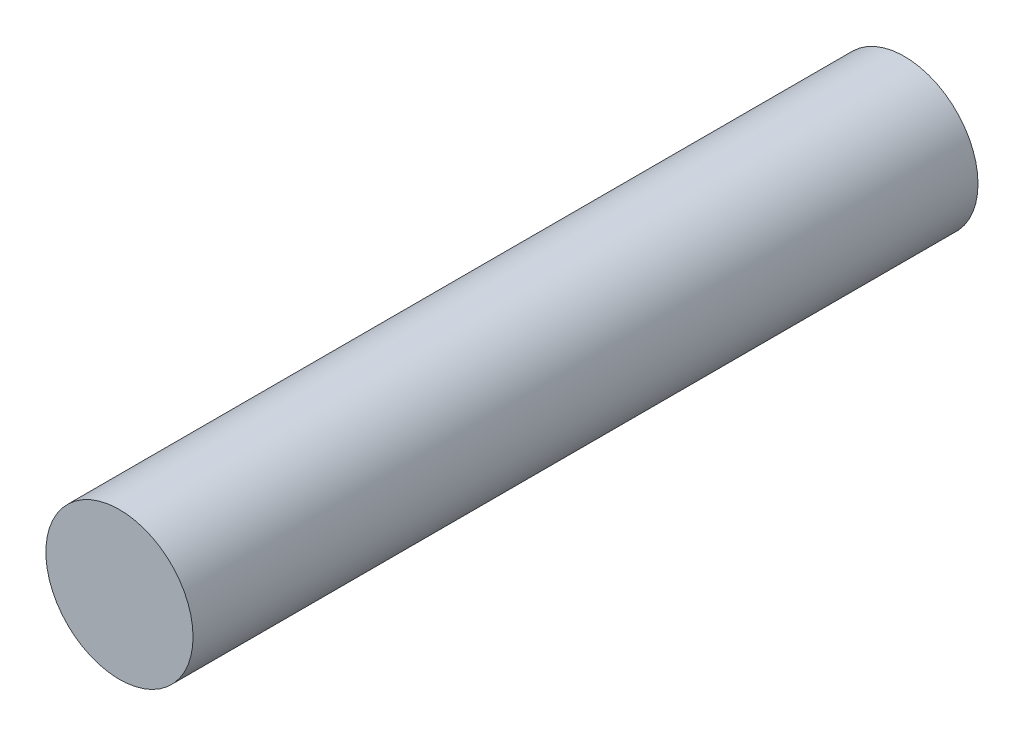
SolidWorks part; units mm, degrees
ref_plane "Front Plane" through (0, 0, 0) normal (0, 0, 1) x (1, 0, 0)
ref_plane "Top Plane" through (0, 0, 0) normal (0, 1, 0) x (1, 0, 0)
ref_plane "Right Plane" through (0, 0, 0) normal (1, 0, 0) x (0, 0, -1)
sketch "Sketch1" plane through (0, 0, 0) normal (0, 0, 1) x (1, 0, 0)
  circle A0 centre (0, 0) radius 4.7625
  dimension "D1" = 9.525
extrude "Boss-Extrude1" add sketch "Sketch1" along normal mid plane 50.8
